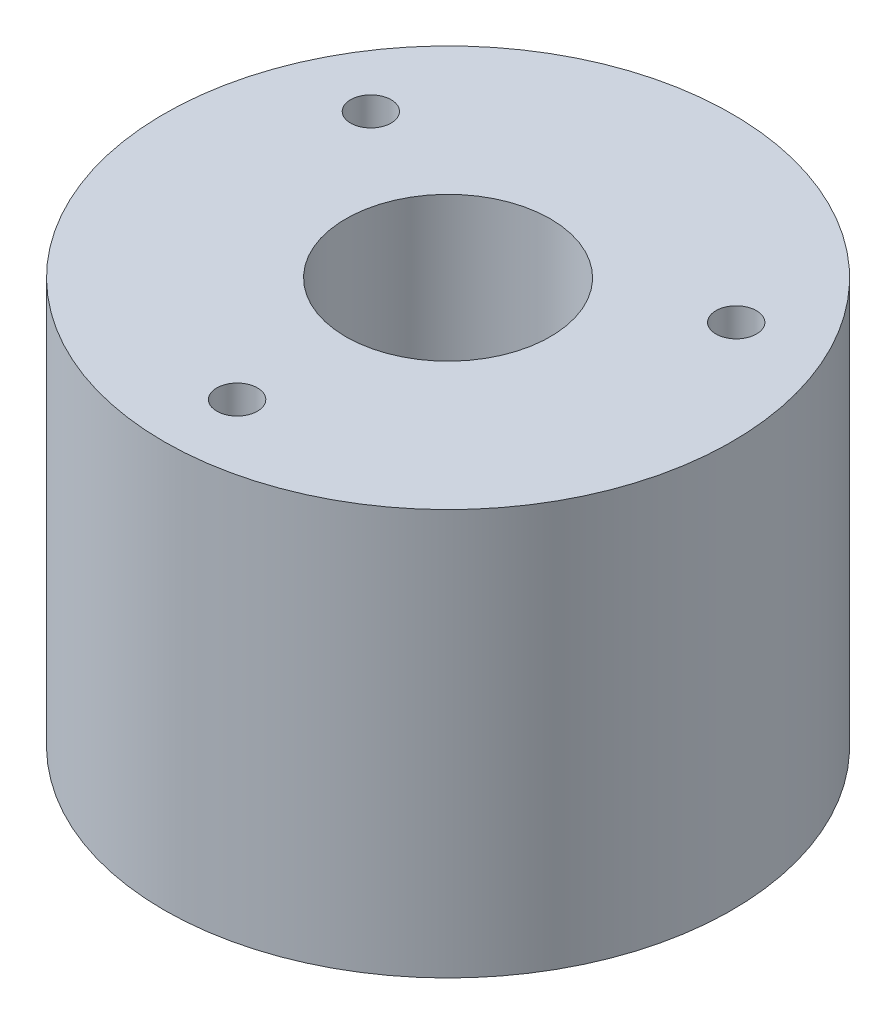
SolidWorks part; units mm, degrees
material "6061-T6 (SS)"
ref_plane "Front Plane" through (0, 0, 0) normal (0, 0, 1) x (1, 0, 0)
ref_plane "Top Plane" through (0, 0, 0) normal (0, 1, 0) x (1, 0, 0)
ref_plane "Right Plane" through (0, 0, 0) normal (1, 0, 0) x (0, 0, -1)
sketch "Sketch1" plane through (0, 0, 0) normal (0, 1, 0) x (1, 0, 0)
  circle A0 centre (0, 0) radius 22.225
  circle A1 centre (0, 0) radius 8.001
  dimension "D1" = 44.45
  dimension "D2" = 16.002
extrude "Boss-Extrude1" add sketch "Sketch1" along normal blind 31.75
sketch "Sketch2" plane through (0, 0, 0) normal (0, -1, 0) x (1, 0, 0)
  line L1 (6.9215, 11.9884) -> (-6.9215, 11.9884)
  line L2 (-6.9215, 11.9884) -> (-13.843, 0)
  line L3 (-13.843, 0) -> (-6.9215, -11.9884)
  line L4 (-6.9215, -11.9884) -> (6.9215, -11.9884)
  line L5 (6.9215, -11.9884) -> (13.843, 0)
  line L6 (13.843, 0) -> (6.9215, 11.9884)
  circle A0 centre (0, 0) radius 11.9884 construction
  circle A1 centre (-6.9215, 11.9884) radius 1.5875
  circle A2 centre (6.9215, 11.9884) radius 1.5875
  circle A3 centre (13.843, 0) radius 1.5875
  circle A4 centre (6.9215, -11.9884) radius 1.5875
  circle A5 centre (-6.9215, -11.9884) radius 1.5875
  circle A6 centre (-13.843, 0) radius 1.5875
  point P22 (0, 0)
  circle M3 centre (0, 0) radius 8.001
  dimension "D2" = 3.175
  dimension "D3" = 6
  dimension "D1" = 13.843
extrude "Cut-Extrude1" cut sketch "Sketch2" against normal blind 9.9219 contours L2 A6 L3 | L3 A6 L2 | A6 L3 A5 L4 A4 L5 A3 L6 A2 L1 A1 L2 M3 | L3 A5 L4 | L4 A5 L3 | L4 A4 L5 | L5 A4 L4 | L5 A3 L6 | L6 A3 L5 | L6 A2 L1 | L1 A2 L6 | L1 A1 L2 | L2 A1 L1
fillet "Fillet1" radius 3.175 12 edges at (-13.0493, 4.9609, -1.3748) (-7.7153, 4.9609, -10.6136) (-5.334, 4.9609, -11.9884) (5.334, 4.9609, -11.9884) (7.7152, 4.9609, -10.6136) (13.0492, 4.9609, -1.3748) (13.0493, 4.9609, 1.3748) (7.7153, 4.9609, 10.6136) (5.334, 4.9609, 11.9884) (-5.334, 4.9609, 11.9884) (-7.7153, 4.9609, 10.6136) (-13.0492, 4.9609, 1.3748)
sketch "Sketch3" plane through (0, 0, 0) normal (0, -1, 0) x (1, 0, 0)
  line L0 (3.3717, 11.9884) -> (-3.3717, 11.9884) construction
  circle A0 centre (0, 16.51) radius 1.5875
  circle A1 centre (14.2981, -8.255) radius 1.5875
  circle A2 centre (-14.2981, -8.255) radius 1.5875
  point P2 (0, 11.9884)
  point P12 (0, 0)
  dimension "D2" = 3.175
  dimension "D1" = 16.51
  dimension "D3" = 3
extrude "Cut-Extrude2" cut sketch "Sketch3" against normal through all
